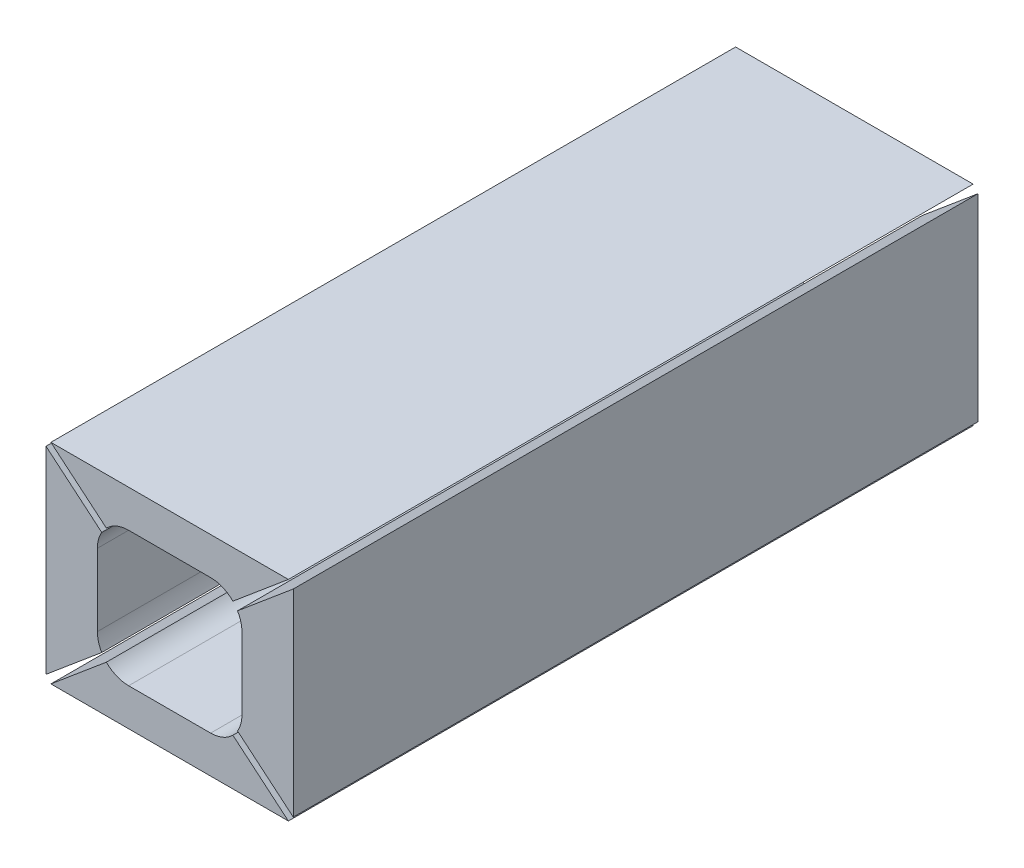
SolidWorks part; units mm, degrees
ref_plane "前视基准面" through (0, 0, 0) normal (0, 0, 1) x (1, 0, 0)
ref_plane "上视基准面" through (0, 0, 0) normal (0, 1, 0) x (1, 0, 0)
ref_plane "右视基准面" through (0, 0, 0) normal (1, 0, 0) x (0, 0, -1)
sketch "草图1" plane through (0, 0, 0) normal (0, 0, 1) x (1, 0, 0)
  line L0 (0, 0) -> (-32.5, 27.2707) construction
  line L3 (31.2175, 27.5) -> (-31.2175, 27.5)
  line L4 (-32.5, -25.9653) -> (-32.5, 25.9653)
  line L5 (19, -9.48) -> (19, 9.48)
  line L6 (17.8503, 13.6728) -> (32.5, 25.9653)
  line L9 (10.78, 17.7) -> (-10.78, 17.7)
  line L10 (-19, -9.48) -> (-19, 9.48)
  line L11 (32.5, -25.9653) -> (32.5, 25.9653)
  line L12 (16.6273, 15.2573) -> (31.2175, 27.5)
  line L13 (-16.6273, 15.2573) -> (-31.2175, 27.5)
  line L14 (-17.8503, 13.6728) -> (-32.5, 25.9653)
  line L15 (-0.6428, -0.766) -> (-33.1428, 26.5047) construction
  line L16 (0.6428, 0.766) -> (-31.8572, 28.0368) construction
  line L17 (-32.5, 27.5) -> (-32.5, 25.9653) construction
  line L18 (-31.2175, 27.5) -> (-32.5, 27.5) construction
  line L19 (0, 0) -> (-32.5, 0) construction
  line L20 (0, 0) -> (0, 27.5) construction
  line L21 (17.8503, -13.6728) -> (32.5, -25.9653)
  line L22 (-17.8503, -13.6728) -> (-32.5, -25.9653)
  line L23 (0, 0) -> (-19, 17.7) construction
  line L24 (0, 0) -> (-32.5, 27.5) construction
  line L25 (16.6273, -15.2573) -> (31.2175, -27.5)
  line L26 (31.2175, -27.5) -> (-31.2175, -27.5)
  line L27 (-16.6273, -15.2573) -> (-31.2175, -27.5)
  line L28 (10.78, -17.7) -> (-10.78, -17.7)
  arc A3 (-10.78, 17.7) -> (-16.6273, 15.2573) centre (-10.78, 9.48) ccw
  arc A4 (-17.8503, 13.6728) -> (-19, 9.48) centre (-10.78, 9.48) ccw
  arc A5 (10.78, 17.7) -> (16.6273, 15.2573) centre (10.78, 9.48) cw
  arc A6 (17.8503, 13.6728) -> (19, 9.48) centre (10.78, 9.48) cw
  arc A7 (17.8503, -13.6728) -> (19, -9.48) centre (10.78, -9.48) ccw
  arc A8 (-17.8503, -13.6728) -> (-19, -9.48) centre (-10.78, -9.48) cw
  arc A9 (10.78, -17.7) -> (16.6273, -15.2573) centre (10.78, -9.48) ccw
  arc A10 (-10.78, -17.7) -> (-16.6273, -15.2573) centre (-10.78, -9.48) cw
  point P0 (0, 0)
  point P2 (0, 0)
  point P4 (0, 17.7)
  point P16 (19, 0)
  point P17 (32.5, 0)
  point P39 (-19, 0)
  dimension "D9" = 8.22
  dimension "D1" = 65
  dimension "D2" = 55
  dimension "D3" = 38
  dimension "D4" = 35.4
  dimension "D6" = 50
  dimension "D7" = 1
  dimension "D8" = 1
extrude "凸台-拉伸1" add sketch "草图1" along normal mid plane 180
